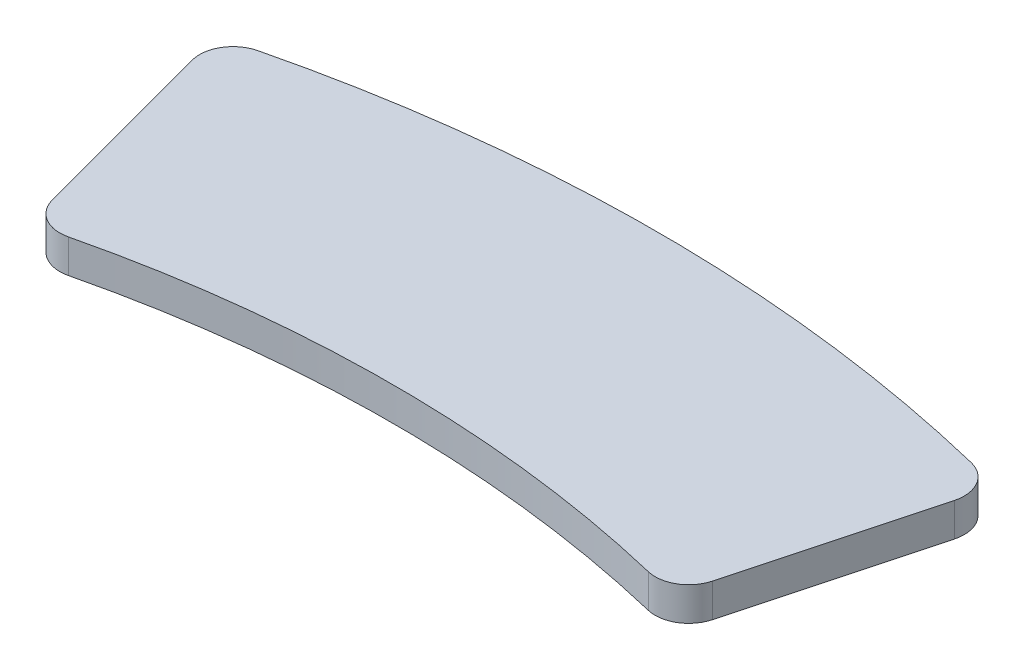
SolidWorks part; units mm, degrees
material "BUTYL"
ref_plane "Front Plane" through (0, 0, 0) normal (0, 0, 1) x (1, 0, 0)
ref_plane "Top Plane" through (0, 0, 0) normal (0, 1, 0) x (1, 0, 0)
ref_plane "Right Plane" through (0, 0, 0) normal (1, 0, 0) x (0, 0, -1)
sketch "Sketch1" plane through (0, 0, 0) normal (0, 1, 0) x (1, 0, 0)
  line L0 (0, 0) -> (0, 90) construction
  line L1 (-23.2937, 86.9333) -> (-19.2044, 71.6717)
  line L2 (23.2937, 86.9333) -> (19.2044, 71.6717)
  circle A0 centre (0, 0) radius 90 construction
  circle A1 centre (0, 0) radius 74.2 construction
  arc A2 (23.2937, 86.9333) -> (-23.2937, 86.9333) centre (0, 0) ccw
  arc A3 (19.2044, 71.6717) -> (-19.2044, 71.6717) centre (0, 0) ccw
  point P7 (0, 74.2)
  dimension "D1" = 180
  dimension "D2" = 148.4
  dimension "D3" = 15
extrude "Boss-Extrude1" add sketch "Sketch1" along normal blind 2
fillet "Fillet1" radius 2 4 edges at (-19.2044, 1, -71.6717) (-23.2937, 1, -86.9333) (23.2937, 1, -86.9333) (19.2044, 1, -71.6717)
